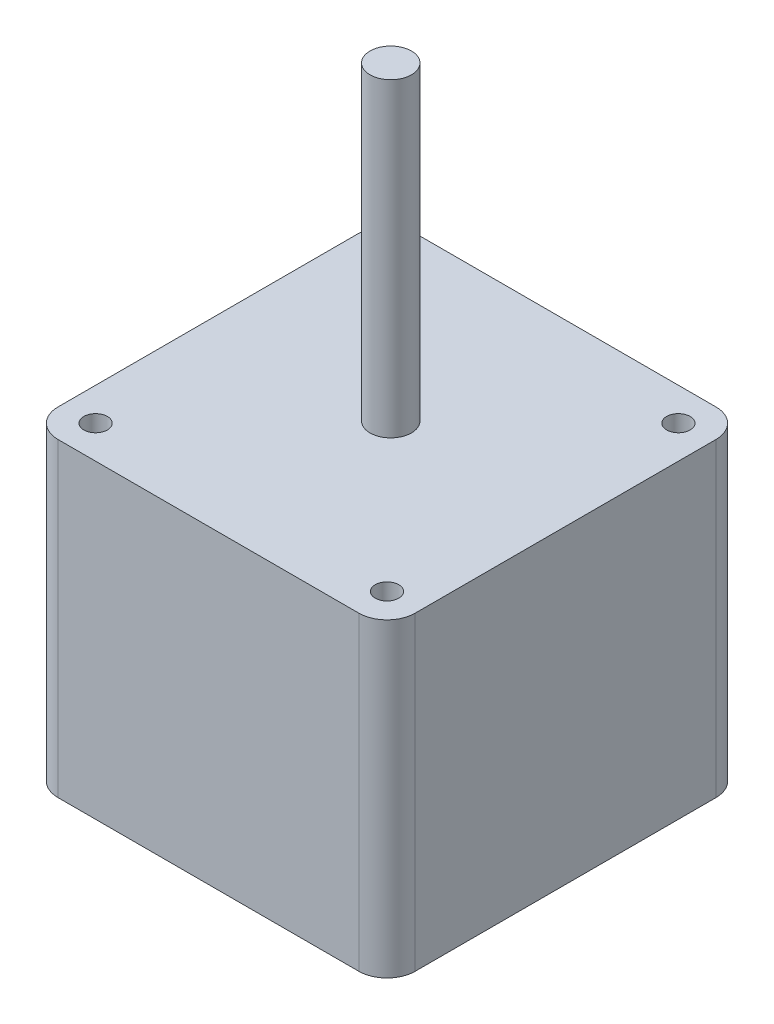
SolidWorks part; units mm, degrees
ref_plane "Front Plane" through (0, 0, 0) normal (0, 0, 1) x (1, 0, 0)
ref_plane "Top Plane" through (0, 0, 0) normal (0, 1, 0) x (1, 0, 0)
ref_plane "Right Plane" through (0, 0, 0) normal (1, 0, 0) x (0, 0, -1)
sketch "Sketch1" plane through (0, 0, 0) normal (0, 1, 0) x (1, 0, 0)
  line L0 (0, 38) -> (0, 0)
  line L1 (0, 0) -> (38, 0)
  line L2 (38, 0) -> (38, 38)
  line L3 (38, 38) -> (0, 38)
  dimension "D1" = 38
  dimension "D2" = 38
extrude "Boss-Extrude1" add sketch "Sketch1" along normal blind 33
sketch "Sketch2" plane through (0, 33, 0) normal (0, 1, 0) x (1, 0, 0)
  circle A0 centre (19, 19.3988) radius 2.2
  dimension "D1" = 4.4
extrude "Boss-Extrude2" add sketch "Sketch2" along normal blind 33
fillet "Fillet1" radius 3 4 edges at (38, 16.5, -38) (38, 16.5, 0) (0, 16.5, 0) (0, 16.5, -38)
ref_plane "Plane1" through (0, 33, 0) normal (0, 1, 0) x (1, 0, 0)
sketch "Sketch3" plane through (0, 33, 0) normal (0, 1, 0) x (1, 0, 0)
  line L0 (19, 38) -> (19, 0)
  line L1 (35, 38) -> (3, 38) construction
  line L2 (3, 0) -> (35, 0) construction
  line L3 (0, 19) -> (38, 19) construction
  line L4 (0, 35) -> (0, 3) construction
  line L5 (38, 3) -> (38, 35) construction
  circle A0 centre (3.5, 34.5) radius 1.25
  circle A1 centre (3.5, 3.5) radius 1.25
  circle A2 centre (34.5, 3.5) radius 1.25
  circle A3 centre (34.5, 34.5) radius 1.25
  dimension "D1" = 2.5
  dimension "D2" = 15.5
  dimension "D3" = 15.5
extrude "Cut-Extrude1" cut sketch "Sketch3" against normal blind 7 contours A0 | A3 | A1 | A2
